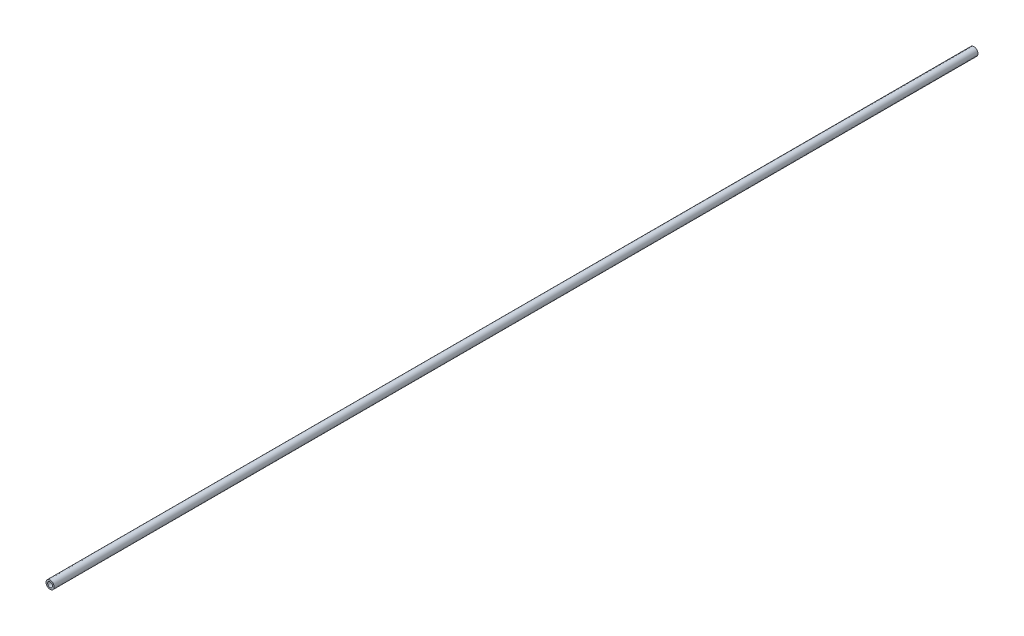
SolidWorks part; units mm, degrees
material "6061-T4 (SS)"
ref_plane "Front Plane" through (0, 0, 0) normal (0, 0, 1) x (1, 0, 0)
ref_plane "Top Plane" through (0, 0, 0) normal (0, 1, 0) x (1, 0, 0)
ref_plane "Right Plane" through (0, 0, 0) normal (1, 0, 0) x (0, 0, -1)
sketch "Sketch2" plane through (0, 0, 0) normal (0, 0, 1) x (1, 0, 0)
  circle A0 centre (0, 0) radius 12.7
  circle A1 centre (0, 0) radius 7.62
  dimension "D2" = 25.4
  dimension "D1" = 5.08
extrude "Boss-Extrude2" add sketch "Sketch2" along normal blind 2874.8567 contours A0
sketch "Sketch4" plane through (0, 0, 0) normal (0, 0, -1) x (-1, 0, 0)
  circle A0 centre (0, 0) radius 7.62
  circle A1 centre (0, 0) radius 12.7 construction
  dimension "D1" = 5.08
extrude "Cut-Extrude2" cut sketch "Sketch4" against normal blind 2874.8567
equation "\"A\" = PI / 4 * ( ( \"d_1\" ^ 2 ) - ( \"d_2\" ^ 2 ) )"
equation "\"d_1\" = 1"
equation "\"d_2\" = \"d_1\" - ( 2 * \"t\" )"
equation "\"t\" = .2"
equation "\"F\"= 400"
equation "\"L\" = ( \"Delta\" * \"E\" * \"A\" ) / \"F\""
equation "\"Delta\" = .009"
equation "\"E\" = 10007604"
equation "\"D1@Sketch2\"=\"t\""
equation "\"D2@Sketch2\"=\"d_1\""
equation "\"D1@Boss-Extrude2\"=\"L\""
equation "\"D1@Sketch4\"=\"t\""
equation "\"D1@Cut-Extrude2\"=\"L\""
